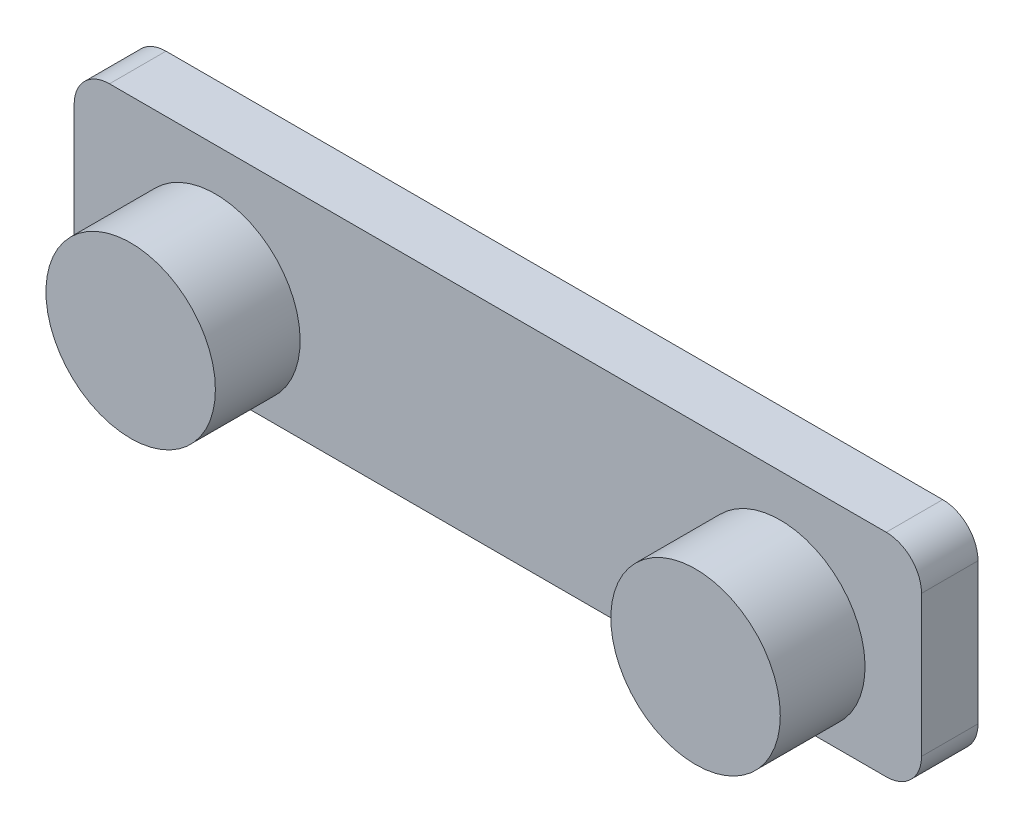
SolidWorks part; units mm, degrees
ref_plane "Front Plane" through (0, 0, 0) normal (0, 0, 1) x (1, 0, 0)
ref_plane "Top Plane" through (0, 0, 0) normal (0, 1, 0) x (1, 0, 0)
ref_plane "Right Plane" through (0, 0, 0) normal (1, 0, 0) x (0, 0, -1)
sketch "草图3" plane through (0, 0, 0) normal (0, 0, 1) x (1, 0, 0)
  line L0 (85, 0) -> (195, 0)
  line L1 (200, 5) -> (200, 25)
  line L2 (195, 30) -> (85, 30)
  line L3 (80, 25) -> (80, 5)
  arc A0 (85, 30) -> (80, 25) centre (85, 25) ccw
  arc A1 (200, 25) -> (195, 30) centre (195, 25) ccw
  arc A2 (195, 0) -> (200, 5) centre (195, 5) ccw
  arc A3 (85, 0) -> (80, 5) centre (85, 5) cw
  point P9 (200, 30)
  point P12 (200, 0)
  point P15 (80, 0)
  dimension "radius" = 5
  dimension "x0" = 80
  dimension "x1" = 200
  dimension "y2" = 30
extrude "BasePlate" add sketch "草图3" along normal blind 8
sketch "草图4" plane through (0, 0, 0) normal (0, 0, 1) x (1, 0, 0)
  circle A0 centre (100, 12) radius 12
  dimension "diameter" = 24
  dimension "x" = 100
  dimension "y" = 12
extrude "PivotA" add sketch "草图4" along normal blind 20
sketch "草图5" plane through (0, 0, 0) normal (0, 0, 1) x (1, 0, 0)
  circle A0 centre (180, 12) radius 12
  dimension "diameter" = 24
  dimension "x" = 180
  dimension "y" = 12
extrude "PivotD" add sketch "草图5" along normal blind 20
